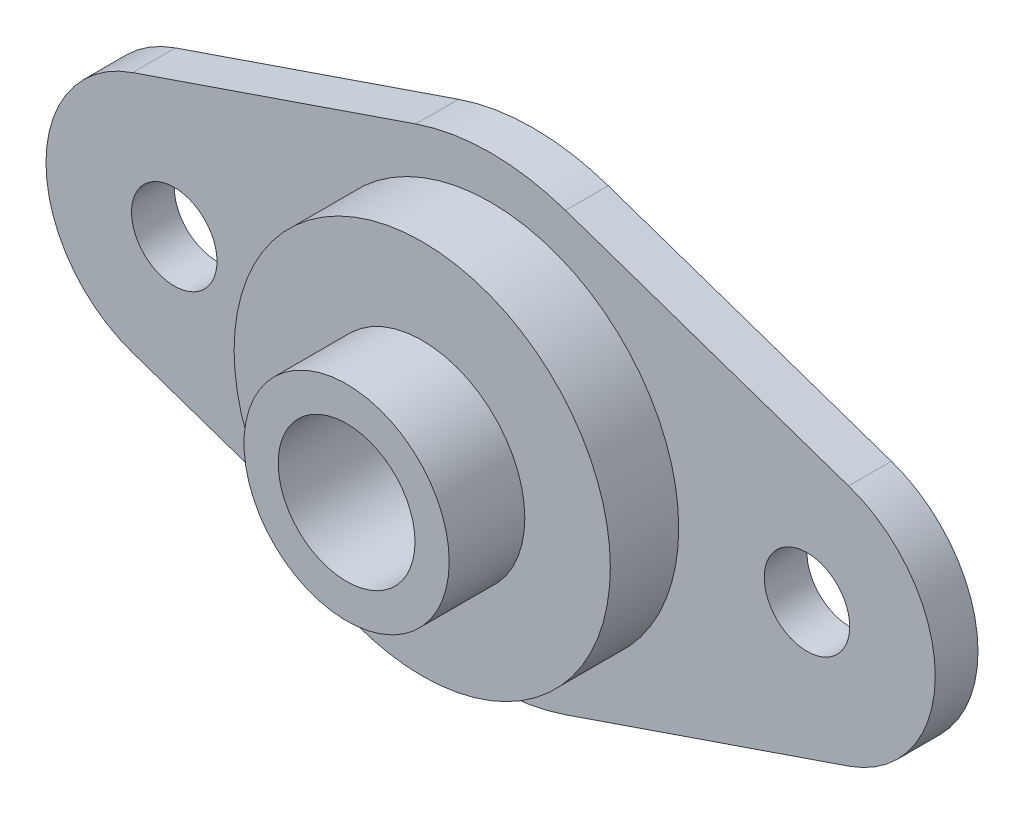
SolidWorks part; units mm, degrees
ref_plane "Front Plane" through (0, 0, 0) normal (0, 0, 1) x (1, 0, 0)
ref_plane "Top Plane" through (0, 0, 0) normal (0, 1, 0) x (1, 0, 0)
ref_plane "Right Plane" through (0, 0, 0) normal (1, 0, 0) x (0, 0, -1)
sketch "Sketch2" plane through (0, 0, 0) normal (0, 0, 1) x (1, 0, 0)
  line L0 (20.9324, 7.0946) -> (4.3784, 12.7703)
  line L1 (20.9324, -7.0946) -> (4.3784, -12.7703)
  line L2 (0, 13.5) -> (0, -13.5) construction
  line L3 (-20.9324, -7.0946) -> (-4.3784, -12.7703)
  line L4 (-20.9324, 7.0946) -> (-4.3784, 12.7703)
  circle A0 centre (0, 0) radius 4
  circle A1 centre (0, 0) radius 13.5
  arc A2 (20.9324, 7.0946) -> (20.9324, -7.0946) centre (18.5, 0) cw
  arc A3 (-20.9324, 7.0946) -> (-20.9324, -7.0946) centre (-18.5, 0) ccw
  circle A4 centre (18.5, 0) radius 2.5
  circle A5 centre (-18.5, 0) radius 2.5
  dimension "D1" = 8
  dimension "D2" = 27
  dimension "D3" = 7.5
  dimension "D5" = 5
  dimension "D4" = 18.5
extrude "Boss-Extrude1" add sketch "Sketch2" along normal blind 2.5 contours L4 A3 L3 A1 | A2 L0 A1 L1 | L2 A1 A0 | A1 L2 A0
sketch "Sketch3" plane through (0, 0, 0) normal (0, 0, 1) x (1, 0, 0)
  circle A0 centre (0, 0) radius 6
  circle A1 centre (0, 0) radius 4
  dimension "D1" = 12
  dimension "D2" = 8
extrude "Boss-Extrude2" add sketch "Sketch3" along normal blind 10.922
ref_plane "Plane1" through (0, 0, 2.5) normal (0, 0, 1) x (1, 0, 0)
sketch "Sketch4" plane through (0, 0, 2.5) normal (0, 0, 1) x (1, 0, 0)
  circle A0 centre (0, 0) radius 11
  circle A1 centre (0, 0) radius 6
  dimension "D1" = 12
  dimension "D2" = 22
extrude "Boss-Extrude3" add sketch "Sketch4" along normal blind 4
